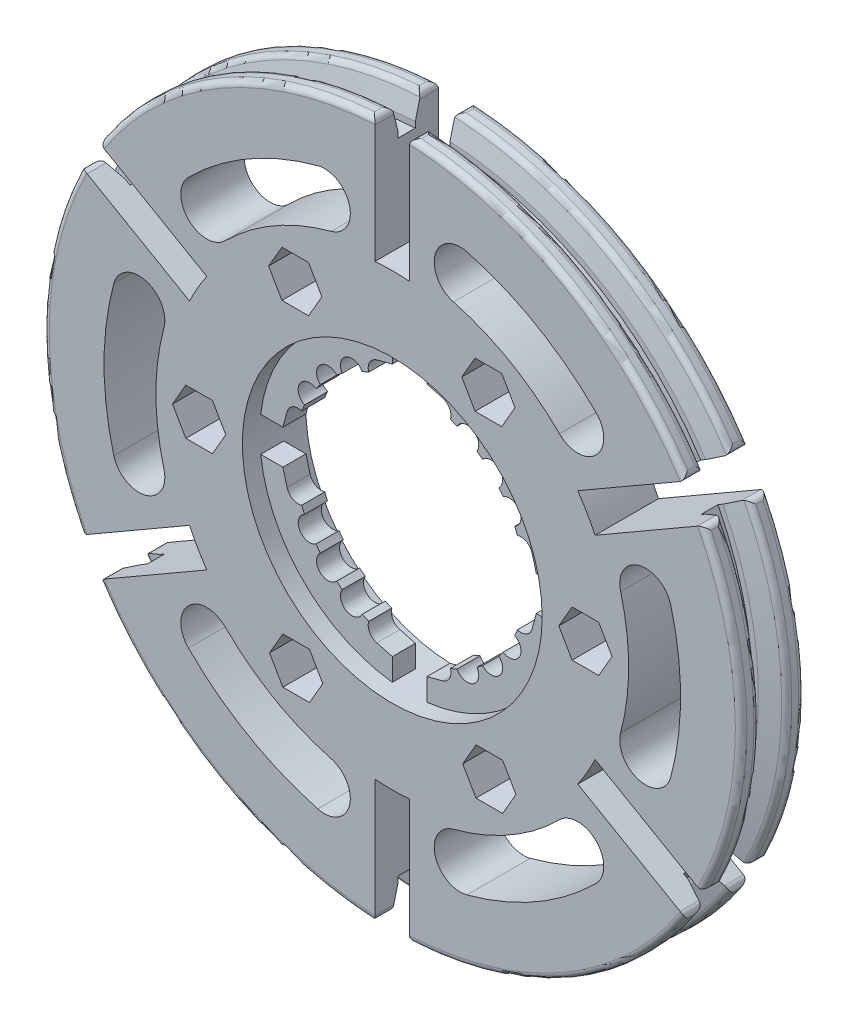
SolidWorks part; units mm, degrees
ref_plane "前视基准面" through (0, 0, 0) normal (0, 0, 1) x (1, 0, 0)
ref_plane "上视基准面" through (0, 0, 0) normal (0, 1, 0) x (1, 0, 0)
ref_plane "右视基准面" through (0, 0, 0) normal (1, 0, 0) x (0, 0, -1)
sketch "草图1" plane through (0, 0, 0) normal (0, 0, 1) x (1, 0, 0)
  line L0 (-1.5, 19.4422) -> (-1.5, 30.2128)
  line L1 (1.5, 19.4422) -> (1.5, 30.2128)
  line L2 (-1.5, -30.2128) -> (-1.5, -19.4422)
  line L4 (1.5, -30.2128) -> (1.5, -19.4422)
  line L5 (-25.415, 16.4054) -> (-16.0875, 11.0201)
  line L7 (-26.915, 13.8074) -> (-17.5875, 8.4221)
  line L9 (26.915, 13.8074) -> (17.5875, 8.4221)
  line L11 (25.415, 16.4054) -> (16.0875, 11.0201)
  line L14 (-17.5875, -8.4221) -> (-26.915, -13.8074)
  line L15 (-16.0875, -11.0201) -> (-25.415, -16.4054)
  line L18 (16.0875, -11.0201) -> (25.415, -16.4054)
  line L19 (17.5875, -8.4221) -> (26.915, -13.8074)
  line L22 (31.8592, 16.6619) -> (30.3592, 19.26) [skipped]
  line L23 (29.1638, -15.1057) -> (27.6638, -17.7038) [skipped]
  line L24 (-27.6638, -17.7038) -> (-29.1638, -15.1057) [skipped]
  line L25 (-30.3592, 19.26) -> (-31.8592, 16.6619) [skipped]
  line L26 (-1.5, 32.8095) -> (1.5, 32.8095) [skipped]
  line L27 (-1.5, -35.9218) -> (1.5, -35.9218) [skipped]
  arc A0 (25.415, 16.4054) -> (1.5, 30.2128) centre (0, 0) ccw
  arc A1 (-16.0875, 11.0201) -> (-17.5875, 8.4221) centre (0, 0) ccw
  arc A2 (26.915, -13.8074) -> (26.915, 13.8074) centre (0, 0) ccw
  arc A3 (-25.415, -16.4054) -> (-1.5, -30.2128) centre (0, 0) ccw
  arc A4 (-26.915, 13.8074) -> (-26.915, -13.8074) centre (0, 0) ccw
  arc A5 (-1.5, 30.2128) -> (-25.415, 16.4054) centre (0, 0) ccw
  arc A6 (1.5, -30.2128) -> (25.415, -16.4054) centre (0, 0) ccw
  arc A7 (-17.5875, -8.4221) -> (-16.0875, -11.0201) centre (0, 0) ccw
  arc A8 (-1.5, -19.4422) -> (1.5, -19.4422) centre (0, 0) ccw
  arc A9 (16.0875, -11.0201) -> (17.5875, -8.4221) centre (0, 0) ccw
  arc A10 (17.5875, 8.4221) -> (16.0875, 11.0201) centre (0, 0) ccw
  arc A11 (1.5, 19.4422) -> (-1.5, 19.4422) centre (0, 0) ccw
  circle A12 centre (0, 0) radius 13
  dimension "D1" = 3
extrude "凸台-拉伸1" add sketch "草图1" against normal blind 5.5
sketch "草图2" plane through (0, 0, 0) normal (0, 0, 1) x (1, 0, 0)
  circle A0 centre (0, 0) radius 27.75
  circle A1 centre (0, 0) radius 30.25
extrude "切除-拉伸1" cut sketch "草图2" against normal blind 1.5 from offset 2 offset against normal yes
chamfer "倒角1" distance 2 distance2 0.5 6 edges at (-15.125, 26.1973, -2) (-30.25, 0, -2) (-15.125, -26.1973, -2) (15.125, -26.1973, -2) (30.25, 0, -2) (15.125, 26.1973, -2)
chamfer "倒角2" distance 0.5 distance2 2 6 edges at (30.25, 0, -3.5) (15.125, 26.1973, -3.5) (-15.125, 26.1973, -3.5) (-30.25, 0, -3.5) (15.125, -26.1973, -3.5) (-15.125, -26.1973, -3.5)
fillet "圆角1" radius 0.5 48 edges at (15.125, 26.1973, -1.5) (15.125, 26.1973, 0) (30.25, 0, -5.5) (26.915, -13.8074, -4.75) (30.25, 0, -4) (26.915, 13.8074, -4.75) (15.125, -26.1973, -5.5) (1.5, -30.2128, -4.75) (15.125, -26.1973, -4) (25.415, -16.4054, -4.75) (-15.125, -26.1973, -5.5) (-25.415, -16.4054, -4.75) (-15.125, -26.1973, -4) (-1.5, -30.2128, -4.75) (-30.25, 0, -5.5) (-26.915, 13.8074, -4.75) (-30.25, 0, -4) (-26.915, -13.8074, -4.75) (15.125, 26.1973, -5.5) (25.415, 16.4054, -4.75) (15.125, 26.1973, -4) (1.5, 30.2128, -4.75) (-15.125, 26.1973, -5.5) (-1.5, 30.2128, -4.75) (-15.125, 26.1973, -4) (-25.415, 16.4054, -4.75) (-15.125, 26.1973, 0) (-25.415, 16.4054, -0.75) (-15.125, 26.1973, -1.5) (-1.5, 30.2128, -0.75) (-30.25, 0, 0) (-26.915, -13.8074, -0.75) (-30.25, 0, -1.5) (-26.915, 13.8074, -0.75) (-15.125, -26.1973, 0) (-1.5, -30.2128, -0.75) (-15.125, -26.1973, -1.5) (-25.415, -16.4054, -0.75) (15.125, -26.1973, 0) (25.415, -16.4054, -0.75) (15.125, -26.1973, -1.5) (1.5, -30.2128, -0.75) (30.25, 0, 0) (26.915, 13.8074, -0.75) (30.25, 0, -1.5) (26.915, -13.8074, -0.75) (1.5, 30.2128, -0.75) (25.415, 16.4054, -0.75)
sketch "草图3" plane through (0, 0, 0) normal (0, 0, 1) x (1, 0, 0)
  arc A0 (14.4957, 14.4957) -> (5.3058, 19.8015) centre (0, 0) ccw
  arc A1 (17.6777, 17.6777) -> (6.4705, 24.1481) centre (0, 0) ccw
  arc A2 (14.4957, 14.4957) -> (17.6777, 17.6777) centre (16.0867, 16.0867) ccw
  arc A3 (6.4705, 24.1481) -> (5.3058, 19.8015) centre (5.8881, 21.9748) ccw
  arc A4 (19.8015, -5.3058) -> (19.8015, 5.3058) centre (0, 0) ccw
  arc A5 (24.1481, -6.4705) -> (24.1481, 6.4705) centre (0, 0) ccw
  arc A6 (19.8015, -5.3058) -> (24.1481, -6.4705) centre (21.9748, -5.8881) ccw
  arc A7 (24.1481, 6.4705) -> (19.8015, 5.3058) centre (21.9748, 5.8881) ccw
  arc A8 (5.3058, -19.8015) -> (14.4957, -14.4957) centre (0, 0) ccw
  arc A9 (6.4705, -24.1481) -> (17.6777, -17.6777) centre (0, 0) ccw
  arc A10 (5.3058, -19.8015) -> (6.4705, -24.1481) centre (5.8881, -21.9748) ccw
  arc A11 (17.6777, -17.6777) -> (14.4957, -14.4957) centre (16.0867, -16.0867) ccw
  arc A12 (-14.4957, -14.4957) -> (-5.3058, -19.8015) centre (0, 0) ccw
  arc A13 (-17.6777, -17.6777) -> (-6.4705, -24.1481) centre (0, 0) ccw
  arc A14 (-14.4957, -14.4957) -> (-17.6777, -17.6777) centre (-16.0867, -16.0867) ccw
  arc A15 (-6.4705, -24.1481) -> (-5.3058, -19.8015) centre (-5.8881, -21.9748) ccw
  arc A16 (-19.8015, 5.3058) -> (-19.8015, -5.3058) centre (0, 0) ccw
  arc A17 (-24.1481, 6.4705) -> (-24.1481, -6.4705) centre (0, 0) ccw
  arc A18 (-19.8015, 5.3058) -> (-24.1481, 6.4705) centre (-21.9748, 5.8881) ccw
  arc A19 (-24.1481, -6.4705) -> (-19.8015, -5.3058) centre (-21.9748, -5.8881) ccw
  arc A20 (-5.3058, 19.8015) -> (-14.4957, 14.4957) centre (0, 0) ccw
  arc A21 (-6.4705, 24.1481) -> (-17.6777, 17.6777) centre (0, 0) ccw
  arc A22 (-5.3058, 19.8015) -> (-6.4705, 24.1481) centre (-5.8881, 21.9748) ccw
  arc A23 (-17.6777, 17.6777) -> (-14.4957, 14.4957) centre (-16.0867, 16.0867) ccw
  dimension "D1" = 6
extrude "切除-拉伸2" cut sketch "草图3" against normal up to next
sketch "草图4" plane through (0, 0, 0) normal (0, 0, 1) x (1, 0, 0)
  line L0 (9.4902, 16.5286) -> (7.1808, 16.5286)
  line L1 (7.1808, 16.5286) -> (6.0261, 14.5286)
  line L2 (6.0261, 14.5286) -> (7.1808, 12.5286)
  line L3 (7.1808, 12.5286) -> (9.4902, 12.5286)
  line L4 (9.4902, 12.5286) -> (10.6449, 14.5286)
  line L5 (-9.5691, 16.4831) -> (-10.7238, 14.4831)
  line L6 (-10.7238, 14.4831) -> (-9.5691, 12.4831)
  line L7 (-9.5691, 12.4831) -> (-7.2597, 12.4831)
  line L8 (-7.2597, 12.4831) -> (-6.105, 14.4831)
  line L9 (-6.105, 14.4831) -> (-7.2597, 16.4831)
  line L10 (-7.2597, 16.4831) -> (-9.5691, 16.4831)
  line L11 (10.6449, 14.5286) -> (9.4902, 16.5286)
  line L12 (19.0593, 0.0455) -> (17.9046, 2.0455)
  line L13 (17.9046, 2.0455) -> (15.5952, 2.0455)
  line L14 (15.5952, 2.0455) -> (14.4405, 0.0455)
  line L15 (14.4405, 0.0455) -> (15.5952, -1.9545)
  line L16 (15.5952, -1.9545) -> (17.9046, -1.9545)
  line L17 (17.9046, -1.9545) -> (19.0593, 0.0455)
  line L18 (9.5691, -16.4831) -> (10.7238, -14.4831)
  line L19 (10.7238, -14.4831) -> (9.5691, -12.4831)
  line L20 (9.5691, -12.4831) -> (7.2597, -12.4831)
  line L21 (7.2597, -12.4831) -> (6.105, -14.4831)
  line L22 (6.105, -14.4831) -> (7.2597, -16.4831)
  line L23 (7.2597, -16.4831) -> (9.5691, -16.4831)
  line L24 (-9.4902, -16.5286) -> (-7.1808, -16.5286)
  line L25 (-7.1808, -16.5286) -> (-6.0261, -14.5286)
  line L26 (-6.0261, -14.5286) -> (-7.1808, -12.5286)
  line L27 (-7.1808, -12.5286) -> (-9.4902, -12.5286)
  line L28 (-9.4902, -12.5286) -> (-10.6449, -14.5286)
  line L29 (-10.6449, -14.5286) -> (-9.4902, -16.5286)
  line L30 (-19.0593, -0.0455) -> (-17.9046, -2.0455)
  line L31 (-17.9046, -2.0455) -> (-15.5952, -2.0455)
  line L32 (-15.5952, -2.0455) -> (-14.4405, -0.0455)
  line L33 (-14.4405, -0.0455) -> (-15.5952, 1.9545)
  line L34 (-15.5952, 1.9545) -> (-17.9046, 1.9545)
  line L35 (-17.9046, 1.9545) -> (-19.0593, -0.0455)
  circle A0 centre (8.3355, 14.5286) radius 2 construction
  circle A1 centre (16.7499, 0.0455) radius 2 construction
  circle A2 centre (8.4144, -14.4831) radius 2 construction
  circle A4 centre (-8.3355, -14.5286) radius 2 construction
  circle A5 centre (-16.7499, -0.0455) radius 2 construction
  circle A8 centre (-8.4144, 14.4831) radius 2 construction
  dimension "D1" = 6
extrude "切除-拉伸3" cut sketch "草图4" against normal up to next
sketch "草图7" plane through (0, 0, 0) normal (0, 0, 1) x (1, 0, 0)
  line L1 (-12.9132, 1.5) -> (-9.8869, 1.5)
  line L2 (-1.5, -9.8869) -> (-1.5, -12.9132)
  line L3 (-12.9132, -1.5) -> (-9.8869, -1.5)
  line L5 (1.5, -9.8869) -> (1.5, -12.9132)
  line L6 (-1.5, 12.9132) -> (-1.5, 9.8869)
  line L7 (9.8869, 1.5) -> (12.9132, 1.5)
  line L8 (1.5, 12.9132) -> (1.5, 9.8869)
  line L10 (9.8869, -1.5) -> (12.9132, -1.5)
  arc A0 (-9.8869, -1.5) -> (-1.5, -9.8869) centre (0, 0) ccw
  arc A1 (-1.5, 12.9132) -> (-12.9132, 1.5) centre (0, 0) ccw
  arc A2 (-1.5, 9.8869) -> (-9.8869, 1.5) centre (0, 0) ccw
  arc A3 (-12.9132, -1.5) -> (-1.5, -12.9132) centre (0, 0) ccw
  arc A4 (9.8869, 1.5) -> (1.5, 9.8869) centre (0, 0) ccw
  arc A5 (1.5, -12.9132) -> (12.9132, -1.5) centre (0, 0) ccw
  arc A6 (12.9132, 1.5) -> (1.5, 12.9132) centre (0, 0) ccw
  arc A8 (1.5, -9.8869) -> (9.8869, -1.5) centre (0, 0) ccw
extrude "凸台-拉伸5" add sketch "草图7" against normal blind 2 from offset 1.5 offset against normal yes
sketch "草图8" plane through (0, 0, -1.5) normal (0, 0, 1) x (1, 0, 0)
  line L0 (2.847, 10.6252) -> (1.5, 10.9861)
  line L1 (1.5, 9.8869) -> (1.5, 10.9861)
  line L3 (-2.847, -10.6252) -> (-1.5, -10.9861)
  line L5 (10.6252, 2.847) -> (10.9861, 1.5)
  line L6 (9.8869, 1.5) -> (10.9861, 1.5)
  line L8 (9.8869, -1.5) -> (10.9861, -1.5)
  line L9 (10.6252, -2.847) -> (10.9861, -1.5)
  line L10 (1.5, -9.8869) -> (1.5, -10.9861)
  line L11 (2.847, -10.6252) -> (1.5, -10.9861)
  line L12 (-1.5, -9.8869) -> (-1.5, -10.9861)
  line L13 (-10.6252, -2.847) -> (-10.9861, -1.5)
  line L14 (-9.8869, -1.5) -> (-10.9861, -1.5)
  line L15 (-9.8869, 1.5) -> (-10.9861, 1.5)
  line L16 (-10.6252, 2.847) -> (-10.9861, 1.5)
  line L17 (-1.5, 9.8869) -> (-1.5, 10.9861)
  line L18 (-2.847, 10.6252) -> (-1.5, 10.9861)
  arc A0 (9.1163, 4.1101) -> (8.1176, 5.8399) centre (0, 0) ccw
  arc A1 (7.7419, 6.3295) -> (6.3295, 7.7419) centre (7.0711, 7.0711) ccw
  arc A2 (9.1163, 4.1101) -> (8.1176, 5.8399) centre (8.6603, 5) ccw
  arc A3 (10.6252, 2.847) -> (9.3525, 3.54) centre (9.6593, 2.5882) ccw
  arc A4 (5.8399, 8.1176) -> (4.1101, 9.1163) centre (5, 8.6603) ccw
  arc A5 (3.54, 9.3525) -> (2.847, 10.6252) centre (2.5882, 9.6593) ccw
  arc A6 (7.7419, 6.3295) -> (6.3295, 7.7419) centre (0, 0) ccw
  arc A7 (5.8399, 8.1176) -> (4.1101, 9.1163) centre (0, 0) ccw
  arc A8 (3.54, 9.3525) -> (1.5, 9.8869) centre (0, 0) ccw
  arc A9 (9.8869, 1.5) -> (9.3525, 3.54) centre (0, 0) ccw
  arc A10 (9.8869, -1.5) -> (9.3525, -3.54) centre (0, 0) cw
  arc A11 (3.54, -9.3525) -> (1.5, -9.8869) centre (0, 0) cw
  arc A12 (5.8399, -8.1176) -> (4.1101, -9.1163) centre (0, 0) cw
  arc A13 (7.7419, -6.3295) -> (6.3295, -7.7419) centre (0, 0) cw
  arc A14 (3.54, -9.3525) -> (2.847, -10.6252) centre (2.5882, -9.6593) cw
  arc A15 (5.8399, -8.1176) -> (4.1101, -9.1163) centre (5, -8.6603) cw
  arc A16 (10.6252, -2.847) -> (9.3525, -3.54) centre (9.6593, -2.5882) cw
  arc A17 (9.1163, -4.1101) -> (8.1176, -5.8399) centre (8.6603, -5) cw
  arc A18 (7.7419, -6.3295) -> (6.3295, -7.7419) centre (7.0711, -7.0711) cw
  arc A19 (9.1163, -4.1101) -> (8.1176, -5.8399) centre (0, 0) cw
  arc A20 (-9.1163, -4.1101) -> (-8.1176, -5.8399) centre (0, 0) ccw
  arc A21 (-7.7419, -6.3295) -> (-6.3295, -7.7419) centre (-7.0711, -7.0711) ccw
  arc A22 (-9.1163, -4.1101) -> (-8.1176, -5.8399) centre (-8.6603, -5) ccw
  arc A23 (-10.6252, -2.847) -> (-9.3525, -3.54) centre (-9.6593, -2.5882) ccw
  arc A24 (-5.8399, -8.1176) -> (-4.1101, -9.1163) centre (-5, -8.6603) ccw
  arc A25 (-3.54, -9.3525) -> (-2.847, -10.6252) centre (-2.5882, -9.6593) ccw
  arc A26 (-7.7419, -6.3295) -> (-6.3295, -7.7419) centre (0, 0) ccw
  arc A27 (-5.8399, -8.1176) -> (-4.1101, -9.1163) centre (0, 0) ccw
  arc A28 (-3.54, -9.3525) -> (-1.5, -9.8869) centre (0, 0) ccw
  arc A29 (-9.8869, -1.5) -> (-9.3525, -3.54) centre (0, 0) ccw
  arc A30 (-9.8869, 1.5) -> (-9.3525, 3.54) centre (0, 0) cw
  arc A31 (-3.54, 9.3525) -> (-1.5, 9.8869) centre (0, 0) cw
  arc A32 (-5.8399, 8.1176) -> (-4.1101, 9.1163) centre (0, 0) cw
  arc A33 (-7.7419, 6.3295) -> (-6.3295, 7.7419) centre (0, 0) cw
  arc A34 (-3.54, 9.3525) -> (-2.847, 10.6252) centre (-2.5882, 9.6593) cw
  arc A35 (-5.8399, 8.1176) -> (-4.1101, 9.1163) centre (-5, 8.6603) cw
  arc A36 (-10.6252, 2.847) -> (-9.3525, 3.54) centre (-9.6593, 2.5882) cw
  arc A37 (-9.1163, 4.1101) -> (-8.1176, 5.8399) centre (-8.6603, 5) cw
  arc A38 (-7.7419, 6.3295) -> (-6.3295, 7.7419) centre (-7.0711, 7.0711) cw
  arc A39 (-9.1163, 4.1101) -> (-8.1176, 5.8399) centre (0, 0) cw
extrude "切除-拉伸4" cut sketch "草图8" against normal up to next
